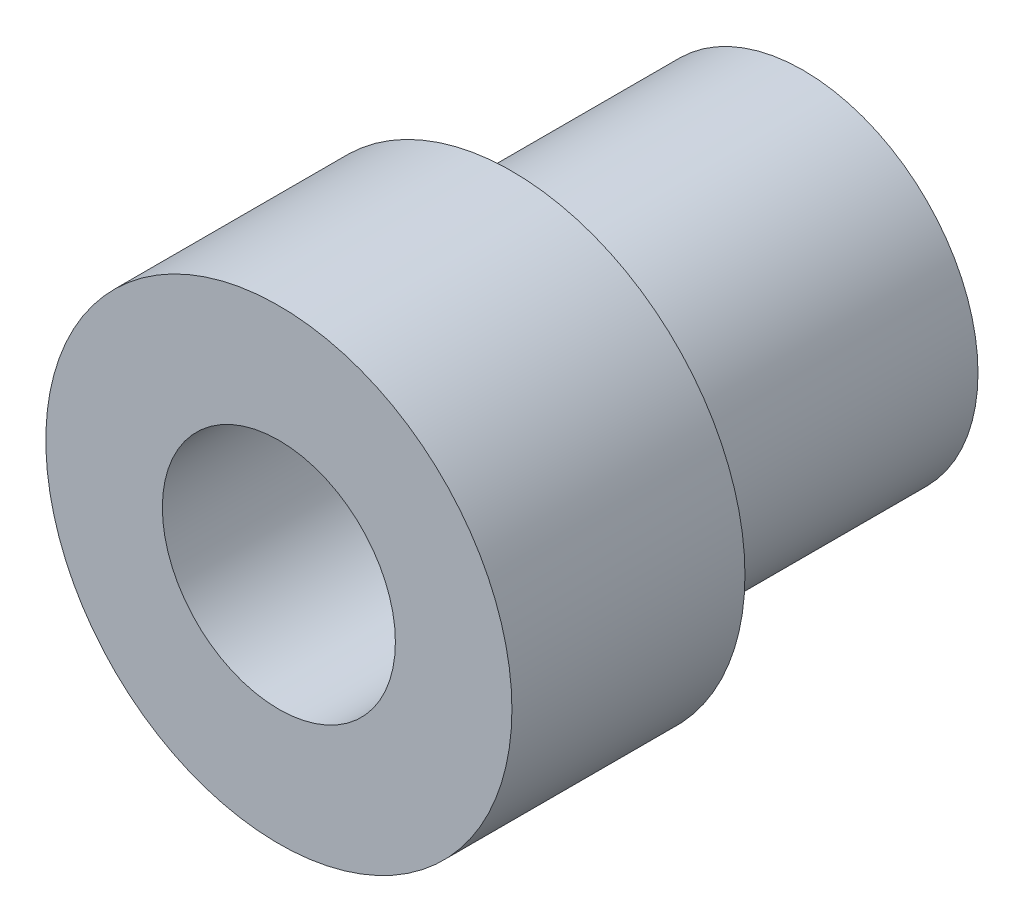
SolidWorks part; units mm, degrees
ref_plane "Front Plane" through (0, 0, 0) normal (0, 0, 1) x (1, 0, 0)
ref_plane "Top Plane" through (0, 0, 0) normal (0, 1, 0) x (1, 0, 0)
ref_plane "Right Plane" through (0, 0, 0) normal (1, 0, 0) x (0, 0, -1)
sketch "Sketch1" plane through (0, 0, 0) normal (0, 0, 1) x (1, 0, 0)
  circle A0 centre (0, 0) radius 6.35
  dimension "D1" = 12.7
extrude "Boss-Extrude1" add sketch "Sketch1" along normal blind 6.35
sketch "Sketch2" plane through (0, 0, 0) normal (0, 0, -1) x (-1, 0, 0)
  circle A0 centre (0, 0) radius 4.7625
  dimension "D1" = 9.525
extrude "Boss-Extrude2" add sketch "Sketch2" along normal blind 7.9375
sketch "Sketch3" plane through (0, 0, -7.9375) normal (0, 0, -1) x (-1, 0, 0)
  circle A0 centre (0, 0) radius 3.175
  dimension "D1" = 6.35
extrude "Cut-Extrude1" cut sketch "Sketch3" against normal up to surface (14.2875 mm away) up to face at (6.35, 0, 6.35)
